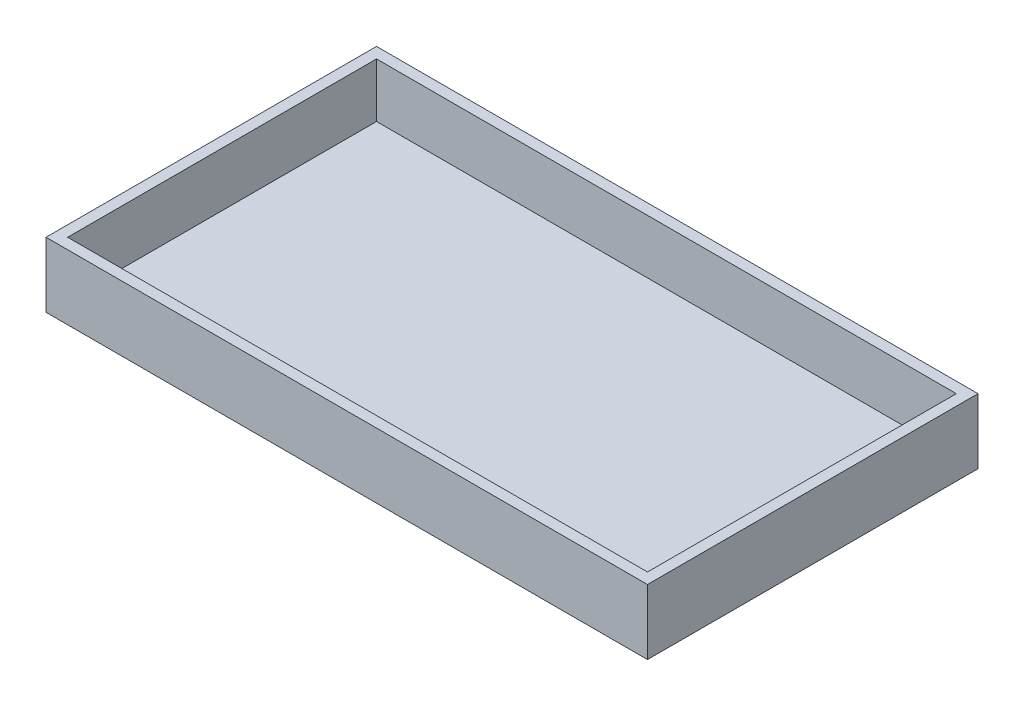
SolidWorks part; units mm, degrees
ref_plane "前基準面" through (0, 0, 0) normal (0, 0, 1) x (1, 0, 0)
ref_plane "上基準面" through (0, 0, 0) normal (0, 1, 0) x (1, 0, 0)
ref_plane "右基準面" through (0, 0, 0) normal (1, 0, 0) x (0, 0, -1)
sketch "草圖1" plane through (0, 0, 0) normal (0, 1, 0) x (1, 0, 0)
  line L1 (0, 0) -> (107, 0)
  line L2 (0, 0) -> (0, 57)
  line L3 (0, 57) -> (107, 57)
  line L4 (107, 0) -> (107, 57)
  dimension "D1" = 57
  dimension "D2" = 107
extrude "伸長-薄件1" add sketch "草圖1" against normal blind 10 thin
sketch "草圖3" plane through (0, -10, 0) normal (0, -1, 0) x (-1, 0, 0)
  line L0 (-109, 59) -> (2, 59) construction
  line L1 (-109, -2) -> (-109, 59) construction
  line L2 (2, -2) -> (-109, -2) construction
  line L3 (2, 59) -> (2, -2) construction
  line L4 (-109, 59) -> (2, 59)
  line L5 (-109, -2) -> (-109, 59)
  line L6 (2, -2) -> (-109, -2)
  line L7 (2, 59) -> (2, -2)
extrude "填料-伸長1" add sketch "草圖3" along normal blind 2
